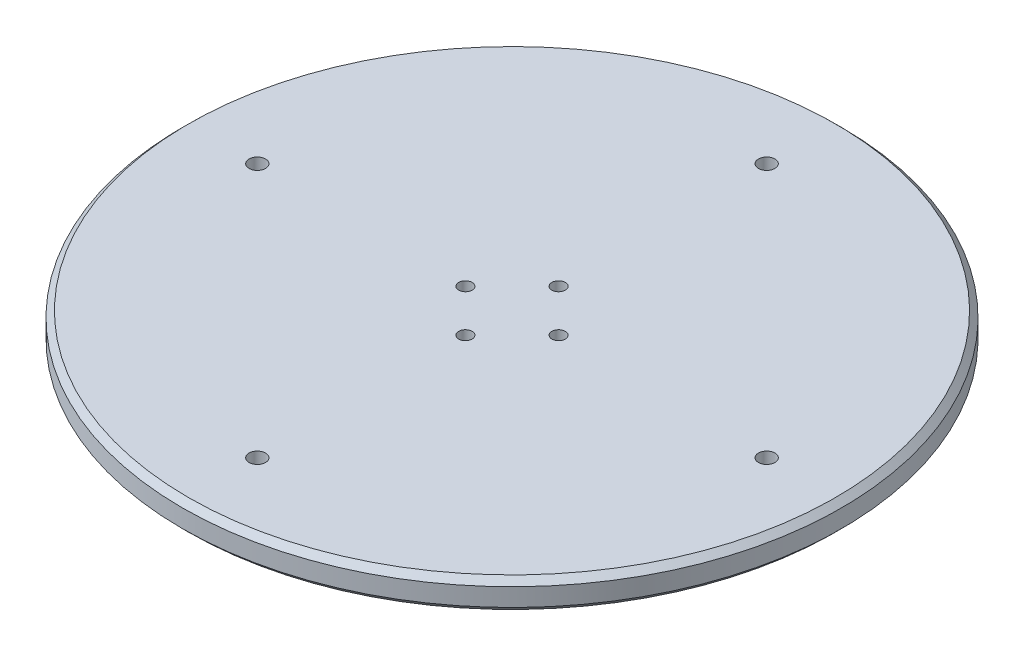
SolidWorks part; units mm, degrees
material "6061-T6 (SS)"
ref_plane "Front Plane" through (0, 0, 0) normal (0, 0, 1) x (1, 0, 0)
ref_plane "Top Plane" through (0, 0, 0) normal (0, 1, 0) x (1, 0, 0)
ref_plane "Right Plane" through (0, 0, 0) normal (1, 0, 0) x (0, 0, -1)
sketch "Sketch3" plane through (0, 0, 0) normal (0, 1, 0) x (1, 0, 0)
  circle A0 centre (0, 0) radius 110
  dimension "D1" = 220
extrude "Boss-Extrude_GB_BaseOD" add sketch "Sketch3" along normal blind 10
sketch "Sketch4" plane through (0, 10, 0) normal (0, 1, 0) x (1, 0, 0)
  circle A1 centre (0, 0) radius 85 construction
  circle A3 centre (-85, 0) radius 2.75
  circle A4 centre (0, 85) radius 2.75
  circle A5 centre (0, 0) radius 85 construction
  circle A6 centre (85, 0) radius 2.75
  circle A7 centre (0, 0) radius 85 construction
  circle A8 centre (0, -85) radius 2.75
  circle A9 centre (0, 0) radius 85 construction
  point P16 (0, 0)
  dimension "D1" = 170
  dimension "D2" = 5.5
  dimension "D3" = 4
extrude "Cut-Extrude1" cut sketch "Sketch4" against normal through all
sketch "Sketch6" plane through (0, 0, 0) normal (0, 1, 0) x (1, 0, 0)
  line L0 (0, 85) -> (85, 0) construction
  line L1 (42.5, 42.5) -> (0, 0) construction
  line L2 (0, 0) -> (-77.7817, -77.7817) construction
  line L3 (-77.7817, -77.7817) -> (77.7817, 77.7817) construction
  line L4 (0, 0) -> (-77.7817, 77.7817) construction
  line L5 (-77.7817, 77.7817) -> (77.7817, -77.7817) construction
  circle A1 centre (0, 0) radius 90 construction
  circle A2 centre (0, 0) radius 70 construction
  circle A4 centre (0, 0) radius 110 construction
  circle A5 centre (0, 0) radius 90 construction
  circle A6 centre (0, 0) radius 90 construction
  circle A7 centre (0, 0) radius 90 construction
  point P6 (63.6396, 63.6396)
  point P20 (63.6396, -63.6396)
  point P22 (-63.6396, -63.6396)
  point P24 (-63.6396, 63.6396)
  point P25 (0, 0)
  dimension "D3" = 4
  dimension "D1" = 180
  dimension "D2" = 140
chamfer "Chamfer1" distance 2 angle 45 2 edges at (0, 0, 110) (0, 10, 110)
sketch "Sketch7" plane through (0, 10, 0) normal (0, 1, 0) x (1, 0, 0)
  line L0 (10.6066, 10.6066) -> (-10.6066, -10.6066) construction
  line L1 (24.7487, -3.5355) -> (-3.5355, 24.7487) construction
  line L2 (3.5355, -24.7487) -> (-24.7487, 3.5355) construction
  line L3 (14.1421, -14.1421) -> (-14.1421, 14.1421) construction
  line L4 (19.0919, -9.1924) -> (9.1924, -19.0919) construction
  line L5 (0, 0) -> (-77.7817, 77.7817) construction
  line L6 (-3.5355, 24.7487) -> (-24.7487, 3.5355) construction
  circle A0 centre (14.8492, 0.7071) radius 2.25
  circle A1 centre (0.7071, 14.8492) radius 2.25
  circle A2 centre (-14.8492, -0.7071) radius 2.25
  circle A3 centre (-0.7071, -14.8492) radius 2.25
  dimension "D1" = 4.5
extrude "Cut-Extrude2" cut sketch "Sketch7" against normal through all
equation "\"____ GENERATED PART EXPORTS ____\" = 0"
equation "\"SYS_VersionTag\" = 2"
equation "\"GB_BaseOD\" = 220mm"
equation "\"GB_BasePlateThk\" = 10mm"
equation "\"GB_BenchMountBCD\" = 170mm"
equation "\"GB_BenchHoleClearDia\" = 5.5mm"
equation "\"GB_BenchMountCount\" = 4"
equation "\"GB_FeetEnabled\" = 1"
equation "\"GB_FeetCount\" = 4"
equation "\"GB_FeetOD\" = 20mm"
equation "\"GB_FeetThk\" = 4mm"
equation "\"GB_FeetBCD\" = 180mm"
equation "\"GB_RemovableBallastEnabled\" = 1"
equation "\"GB_RemovableBallastMountBCD\" = 140mm"
equation "\"GB_RemovableBallastMountClearDia\" = 5.5mm"
equation "\"GB_RemovableBallastMountCount\" = 4"
equation "\"D1@Sketch3\"=\"GB_BaseOD\""
equation "\"D1@Boss-Extrude_GB_BaseOD\" = \"GB_BasePlateThk\""
equation "\"D1@Sketch4\"=\"GB_BenchMountBCD\""
equation "\"D1@Sketch6\"=\"GB_FeetBCD\""
equation "\"D2@Sketch6\"=\"GB_RemovableBallastMountBCD\""
equation "\"D2@Sketch4\"=\"GB_BenchHoleClearDia\""
